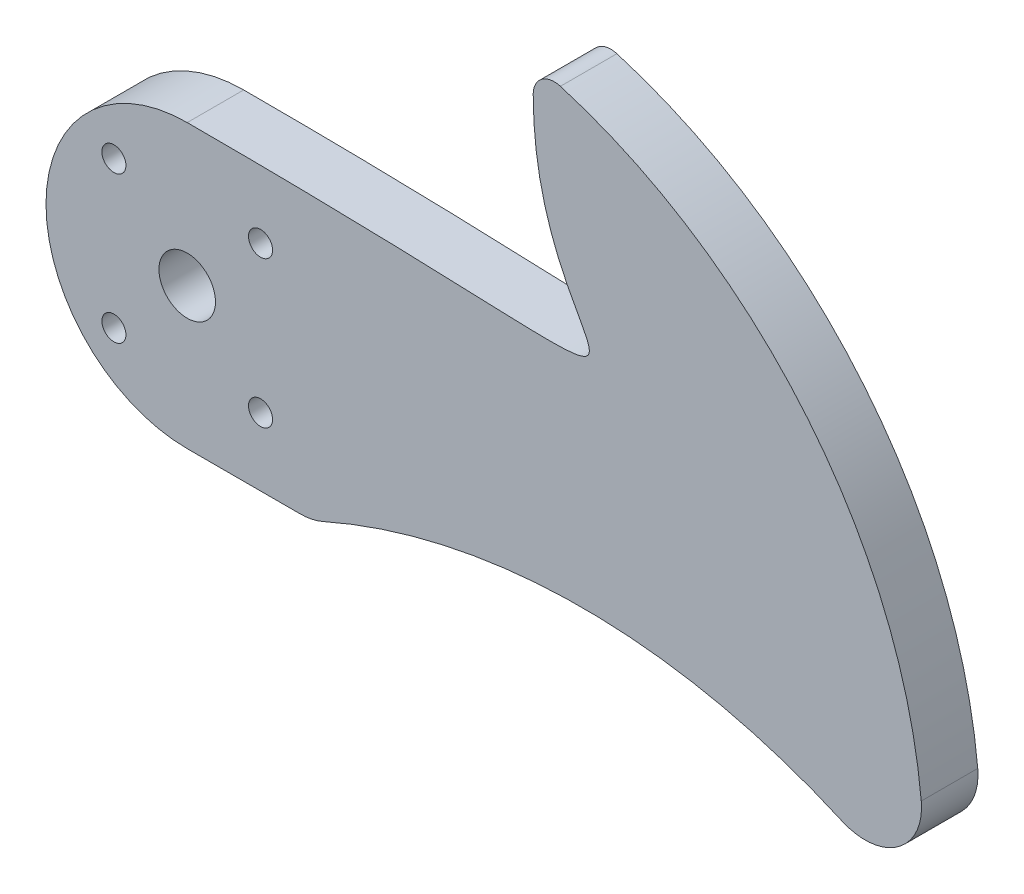
SolidWorks part; units mm, degrees
material "6061 Alloy"
ref_plane "Front" through (0, 0, 0) normal (0, 0, 1) x (1, 0, 0)
ref_plane "Top" through (0, 0, 0) normal (0, 1, 0) x (1, 0, 0)
ref_plane "Right" through (0, 0, 0) normal (1, 0, 0) x (0, 0, -1)
sketch "Sketch1" plane through (0, 0, 0) normal (0, 0, 1) x (1, 0, 0)
  line L0 (0, -15.875) -> (12.7, -15.875)
  line L2 (8.2424, 8.2424) -> (-8.2424, -8.2424) construction
  line L3 (-8.2424, 8.2424) -> (8.2424, -8.2424) construction
  line L4 (0, 0) -> (0, -43.6829) construction
  line L5 (0, -21.8415) -> (119.7815, -21.8415) construction
  line L6 (-8.2424, -51.9253) -> (8.2424, -35.4405) construction
  line L7 (8.2424, -51.9253) -> (-8.2424, -35.4405) construction
  line L8 (3.1238, -59.2475) -> (101.5979, -39.4838) construction
  line L9 (0, -27.8079) -> (101.5979, -27.8079) construction
  line L11 (-22.2168, 15.875) -> (22.2168, 15.875) construction
  line L12 (38.8937, 29.9495) -> (38.8937, 72.4954) construction
  arc A0 (0, 15.875) -> (0, -15.875) centre (0, 0) ccw
  circle A1 centre (0, 0) radius 3.175
  circle A6 centre (0, 0) radius 11.6565 construction
  circle A7 centre (8.2424, 8.2424) radius 1.3525 construction
  circle A8 centre (-8.2424, 8.2424) radius 1.3525 construction
  circle A9 centre (-8.2424, -8.2424) radius 1.3525 construction
  circle A10 centre (8.2424, -8.2424) radius 1.3525 construction
  circle A12 centre (8.2424, -35.4405) radius 1.3525 construction
  circle A13 centre (-8.2424, -35.4405) radius 1.3525 construction
  circle A14 centre (-8.2424, -51.9253) radius 1.3526 construction
  circle A15 centre (8.2424, -51.9253) radius 1.3525 construction
  circle A16 centre (0, -43.6829) radius 11.6565 construction
  arc A17 (101.5979, -27.8079) -> (101.5979, -39.4838) centre (101.5979, -33.6458) cw construction
  circle A18 centre (0, -43.6829) radius 3.175 construction
  arc A19 (3.1238, -59.2475) -> (0, -27.8079) centre (0, -43.6829) cw construction
  circle A20 centre (44.45, -21.8415) radius 25.4 construction
  arc A21 (41.9551, 40.3821) -> (82.5208, -8.9172) centre (25.6333, -14.3876) cw
  arc A25 (41.9551, 40.3821) -> (38.8937, 38.1) centre (41.275, 38.1) ccw
  arc A27 (15.2775, -15.3284) -> (73.6225, -15.3284) centre (44.45, -81.0121) cw
  circle A28 centre (44.45, -21.8415) radius 12.7 construction
  arc A29 (12.7, -15.875) -> (15.2775, -15.3284) centre (12.7, -9.525) ccw
  arc A30 (73.6225, -15.3284) -> (82.5208, -8.9172) centre (76.2, -9.525) ccw
  spline S0 degree 3 poles (38.8937, 38.1) (38.8937, 8.2406) (68.3426, 15.875) (0, 15.875) knots 0 0 0 0 1 1 1 1
  dimension "D1" = 6.35
  dimension "D2" = 31.75
  dimension "D3" = 6.35
  dimension "D4" = 57.15
  dimension "D5" = 43.6829
  dimension "D6" = 50.8
  dimension "D7" = 23.313
  dimension "D8" = 2.7051
  dimension "D10" = 82.55
  dimension "D11" = 63.5
  dimension "D12" = 4.7625
  dimension "D13" = 89.5781
  dimension "D14" = 205.0277
  dimension "D16" = 34.925
  dimension "D17" = 25.4
  dimension "D9" = 38.1
extrude "Boss-Extrude1" add sketch "Sketch1" along normal blind 6.35
hole_wizard "#6-32 Tapped Hole1" positions "Sketch2" profile "Sketch3" tap size "#6-32" standard "ANSI Inch" end condition through all
sketch "Sketch2" plane through (0, 0, 6.35) normal (0, 0, 1) x (1, 0, 0)
  point P0 (8.2424, 8.2424)
  point P3 (-8.2424, 8.2424)
  point P6 (8.2424, -8.2424)
  point P9 (-8.2424, -8.2424)
sketch "Sketch3" plane through (8.2424, 8.2424, 6.35) normal (1, 0, 0) x (0, -1, 0)
  line L0 (0, 0) -> (0, 6.35)
  line L1 (0, 6.35) -> (1.3525, 6.35)
  line L2 (1.3525, 6.35) -> (1.3525, 0)
  line L5 (1.3525, 0) -> (0, 0)
  line L11 (0, -6.35) -> (0, 107.95) construction
  dimension "Thru Tap Drill Dia." = 2.7051
  dimension "Thru Tap Drill Depth" = 6.35
sketch "Sketch4" [suppressed] plane through (0, 0, 6.35) normal (0, 0, 1) x (1, 0, 0)
  circle A0 centre (0, 0) radius 3.175
  circle A1 centre (0, 0) radius 7
  dimension "D1" = 6.35
  dimension "D2" = 14
extrude "Boss-Extrude2" [suppressed] add sketch "Sketch4" along normal blind 1.5875
sketch "Sketch5" plane through (0, 0, 0) normal (0, 0, -1) x (-1, 0, 0)
  circle A0 centre (0, 0) radius 7
  circle A2 centre (0, 0) radius 3.175 construction
  circle A3 centre (0, 0) radius 3.175
  dimension "D2" = 14
extrude "Boss-Extrude3" add sketch "Sketch5" along normal blind 1.5875
sketch "Sketch6" plane through (0, 0, 6.35) normal (0, 0, 1) x (1, 0, 0)
  line L0 (68.326, -15.419) -> (72.3338, -12.2975)
  line L1 (72.3338, -12.2975) -> (73.0332, -17.3291)
  line L2 (68.326, -15.419) -> (73.0332, -17.3291)
  line L3 (72.3338, -12.2975) -> (71.4742, -14.4157) construction
  line L4 (70.2513, -13.9194) -> (72.6972, -14.912) construction
  circle A0 centre (44.45, -81.0121) radius 71.8706 construction
  arc A1 (73.6225, -15.3284) -> (82.5208, -8.9172) centre (76.2, -9.525) ccw construction
  arc A2 (73.6225, -15.3284) -> (15.2775, -15.3284) centre (44.45, -81.0121) ccw construction
  point P10 (71.4742, -14.4157)
  dimension "D1" = 2.286
  dimension "D2" = 2.54
  dimension "D3" = 5.08
extrude "Cut-Extrude1" [suppressed] cut sketch "Sketch6" against normal through all and the other way through all
pattern_curve "CrvPattern1" [suppressed] parameters "D1"=25, "D3"=50, "D2"=1, "D4"=50
